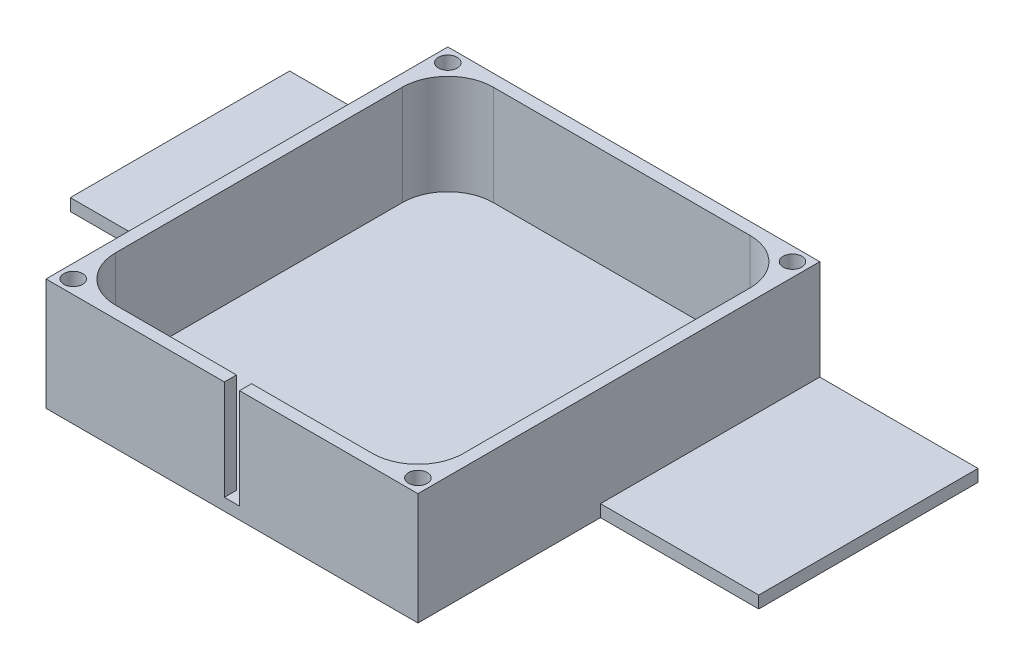
SolidWorks part; units mm, degrees
ref_plane "Front Plane" through (0, 0, 0) normal (0, 0, 1) x (1, 0, 0)
ref_plane "Top Plane" through (0, 0, 0) normal (0, 1, 0) x (1, 0, 0)
ref_plane "Right Plane" through (0, 0, 0) normal (1, 0, 0) x (0, 0, -1)
sketch "Sketch1" plane through (0, 0, 0) normal (0, 1, 0) x (1, 0, 0)
  line L1 (42.2796, -55.1291) -> (42.2796, -47.1291)
  line L2 (42.2796, -47.1291) -> (64.0437, -47.1291)
  line L3 (64.0437, -55.1291) -> (64.0437, -47.1291)
  line L4 (53.1617, -47.1291) -> (53.1617, -16.1356) construction
  line L5 (64.0437, -55.1291) -> (110.0996, -55.1291)
  line L6 (-3.5504, -55.1291) -> (42.2796, -55.1291)
  line L7 (-3.5504, -55.1291) -> (-3.5504, -91.3291)
  line L8 (-3.5504, -91.3291) -> (110.0996, -91.3291)
  line L9 (110.0996, -55.1291) -> (110.0996, -91.3291)
  line L19 (22.5746, -55.1291) -> (83.9746, -55.1291)
  line L20 (22.5746, -55.1291) -> (22.5746, -121.4691)
  line L21 (22.5746, -121.4691) -> (83.9746, -121.4691)
  line L22 (83.9746, -55.1291) -> (83.9746, -121.4691)
  line L23 (22.5746, -55.1291) -> (83.9746, -121.4691) construction
  line L24 (22.5746, -121.4691) -> (83.9746, -55.1291) construction
  circle A0 centre (46.2796, -51.1291) radius 1.55
  circle A1 centre (60.0437, -51.1291) radius 1.55
  point P14 (53.2746, -88.2991)
  point P18 (53.2746, -88.2991)
  dimension "D1" = 3.1
  dimension "D7" = 4
  dimension "D2" = 0
  dimension "D3" = 4
  dimension "D4" = 113.65
  dimension "D5" = 36.2
  dimension "D6" = 66.34
  dimension "D8" = 8
  dimension "D10" = 61.4
extrude "Boss-Extrude1" add sketch "Sketch1" along normal blind 2
sketch "Sketch2" plane through (0, 2, 0) normal (0, 1, 0) x (1, 0, 0)
  line L12 (22.5746, -121.4691) -> (83.9746, -121.4691)
  line L13 (22.5746, -121.4691) -> (22.5746, -55.1291)
  line L14 (22.5746, -55.1291) -> (83.9746, -55.1291)
  line L15 (83.9746, -121.4691) -> (83.9746, -55.1291)
  line L16 (83.9746, -91.3291) -> (83.9746, -121.4691) construction
  line L18 (24.5746, -119.4691) -> (24.5746, -57.1291)
  line L19 (24.5746, -57.1291) -> (81.9746, -57.1291)
  line L20 (81.9746, -119.4691) -> (81.9746, -57.1291)
  line L21 (24.5746, -119.4691) -> (81.9746, -119.4691)
  line L23 (52.0246, -117.4691) -> (54.5246, -117.4691)
  line L24 (52.0246, -117.4691) -> (52.0246, -121.4691)
  line L25 (52.0246, -121.4691) -> (54.5246, -121.4691)
  line L26 (54.5246, -117.4691) -> (54.5246, -121.4691)
  line L27 (52.0246, -117.4691) -> (54.5246, -121.4691) construction
  line L28 (52.0246, -121.4691) -> (54.5246, -117.4691) construction
  point P0 (53.2746, -119.4691)
  line M16 (110.0996, -55.1291) -> (64.0437, -55.1291)
  line M28 (42.2796, -55.1291) -> (-3.5504, -55.1291)
  line M31 (22.5746, -91.3291) -> (22.5746, -121.4691)
  line M32 (22.5746, -121.4691) -> (83.9746, -121.4691)
  line M33 (83.9746, -121.4691) -> (83.9746, -91.3291)
  dimension "D1" = 2.5
  dimension "D4" = 2
extrude "Boss-Extrude2" add sketch "Sketch2" along normal blind 16.5 contours L21 L26 L15 L14 L13 L24 L18 L19 L20 M32 M33 M16 M28 M31
fillet "Fillet1" radius 7.5 4 edges at (24.5746, 10.25, 119.4691) (81.9746, 10.25, 119.4691) (81.9746, 10.25, 57.1291) (24.5746, 10.25, 57.1291)
sketch "Sketch3" plane through (0, 18.5, 0) normal (0, 1, 0) x (1, 0, 0)
  line L2 (22.5746, -91.3291) -> (22.5746, -55.1291) construction
  line L6 (53.2746, -55.1291) -> (53.2746, -121.4691) construction
  line L7 (83.9746, -55.1291) -> (22.5746, -55.1291) construction
  line L8 (52.0246, -121.4691) -> (54.5246, -121.4691) construction
  line L9 (22.5746, -88.2991) -> (83.9746, -88.2991) construction
  line L10 (22.5746, -121.4691) -> (22.5746, -55.1291) construction
  line L11 (83.9746, -121.4691) -> (83.9746, -55.1291) construction
  circle A4 centre (24.8246, -57.3791) radius 1.55
  circle A5 centre (81.7246, -57.3791) radius 1.55
  circle A6 centre (81.7246, -119.2191) radius 1.55
  circle A7 centre (24.8246, -119.2191) radius 1.55
  dimension "D4" = 3.1
  dimension "D5" = 2.25
  dimension "D6" = 2.25
extrude "Cut-Extrude1" cut sketch "Sketch3" against normal blind 10 contours A4 | A5 | A6 | A7
